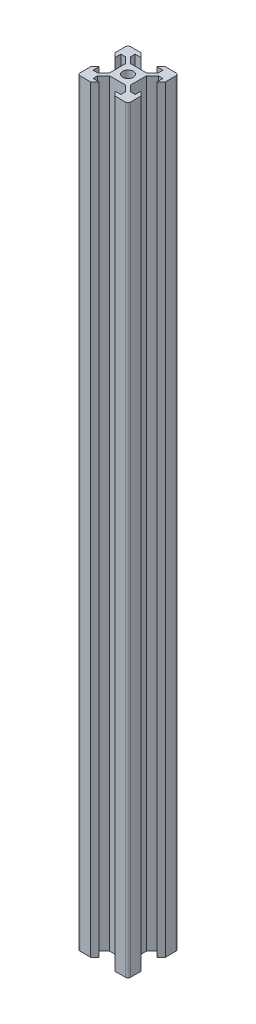
SolidWorks part; units mm, degrees
material "1060 Alloy"
ref_plane "Front Plane" through (0, 0, 0) normal (0, 0, 1) x (1, 0, 0)
ref_plane "Top Plane" through (0, 0, 0) normal (0, 1, 0) x (1, 0, 0)
ref_plane "Right Plane" through (0, 0, 0) normal (1, 0, 0) x (0, 0, -1)
ref_plane "End Plane" through (0, 300, 0) normal (0, 1, 0) x (1, 0, 0)
sketch "MasterLayoutSketch" plane through (0, 0, 0) normal (0, 1, 0) x (1, 0, 0)
  line L0 (-8.325, 3.1) -> (-8.325, 5.5)
  line L1 (-10, -10) -> (10, -10) construction
  line L2 (-10, -10) -> (-10, 10) construction
  line L3 (-10, 10) -> (10, 10) construction
  line L4 (10, -10) -> (10, 10) construction
  line L5 (-10, -10) -> (10, 10) construction
  line L6 (-10, 10) -> (10, -10) construction
  line L7 (-4.775, 10) -> (-3.1, 8.325)
  line L10 (-8.325, 5.5) -> (-6.5607, 5.5)
  line L11 (-10, 4.775) -> (-8.325, 3.1)
  line L12 (-5.5, 8.325) -> (-5.5, 6.5607)
  line L13 (-3.1, 8.325) -> (-5.5, 8.325)
  line L14 (-10, 10) -> (-10, 4.775)
  line L19 (3.1, 8.325) -> (5.5, 8.325)
  line L20 (10, 4.775) -> (8.325, 3.1)
  line L21 (-10, 10) -> (-4.775, 10)
  line L22 (-6.5607, 5.5) -> (-4.1607, 3.1)
  line L23 (-5.5, 6.5607) -> (-3.1, 4.1607)
  line L24 (5.5, 8.325) -> (5.5, 6.5607)
  line L25 (4.775, 10) -> (3.1, 8.325)
  line L26 (8.325, 5.5) -> (6.5607, 5.5)
  line L27 (8.325, 3.1) -> (8.325, 5.5)
  line L28 (10, 10) -> (4.775, 10)
  line L29 (10, 10) -> (10, 4.775)
  line L30 (5.5, 6.5607) -> (3.1, 4.1607)
  line L31 (6.5607, 5.5) -> (4.1607, 3.1)
  line L32 (8.325, -3.1) -> (8.325, -5.5)
  line L33 (4.775, -10) -> (3.1, -8.325)
  line L34 (8.325, -5.5) -> (6.5607, -5.5)
  line L35 (10, -4.775) -> (8.325, -3.1)
  line L36 (5.5, -8.325) -> (5.5, -6.5607)
  line L37 (3.1, -8.325) -> (5.5, -8.325)
  line L38 (10, -10) -> (10, -4.775)
  line L39 (10, -10) -> (4.775, -10)
  line L40 (6.5607, -5.5) -> (4.1607, -3.1)
  line L41 (5.5, -6.5607) -> (3.1, -4.1607)
  line L42 (-3.1, -8.325) -> (-5.5, -8.325)
  line L43 (-10, -4.775) -> (-8.325, -3.1)
  line L44 (-5.5, -8.325) -> (-5.5, -6.5607)
  line L45 (-4.775, -10) -> (-3.1, -8.325)
  line L46 (-8.325, -5.5) -> (-6.5607, -5.5)
  line L47 (-8.325, -3.1) -> (-8.325, -5.5)
  line L48 (-10, -10) -> (-4.775, -10)
  line L49 (-10, -10) -> (-10, -4.775)
  line L50 (-5.5, -6.5607) -> (-3.1, -4.1607)
  line L51 (-6.5607, -5.5) -> (-4.1607, -3.1)
  line L52 (-4.1607, 3.1) -> (-4.1607, -3.1)
  line L53 (-3.1, -4.1607) -> (3.1, -4.1607)
  line L54 (4.1607, -3.1) -> (4.1607, 3.1)
  line L55 (-3.1, 4.1607) -> (3.1, 4.1607)
  circle A0 centre (0, 0) radius 2.1
  point P0 (0, 0)
  point P9 (0, 0)
  dimension "D6" = 4.2
  dimension "D1" = 20
  dimension "D2" = 4
  dimension "D3" = 11
  dimension "D4" = 9.55
  dimension "D5" = 6.2
  dimension "D7" = 1.5
extrude "Main Extrusion" add sketch "MasterLayoutSketch" along normal up to surface (300 mm away) up to plane "End Plane"
fillet "Edge Fillets" radius 1 4 edges at (10, 150, -10) (10, 150, 10) (-10, 150, 10) (-10, 150, -10)
